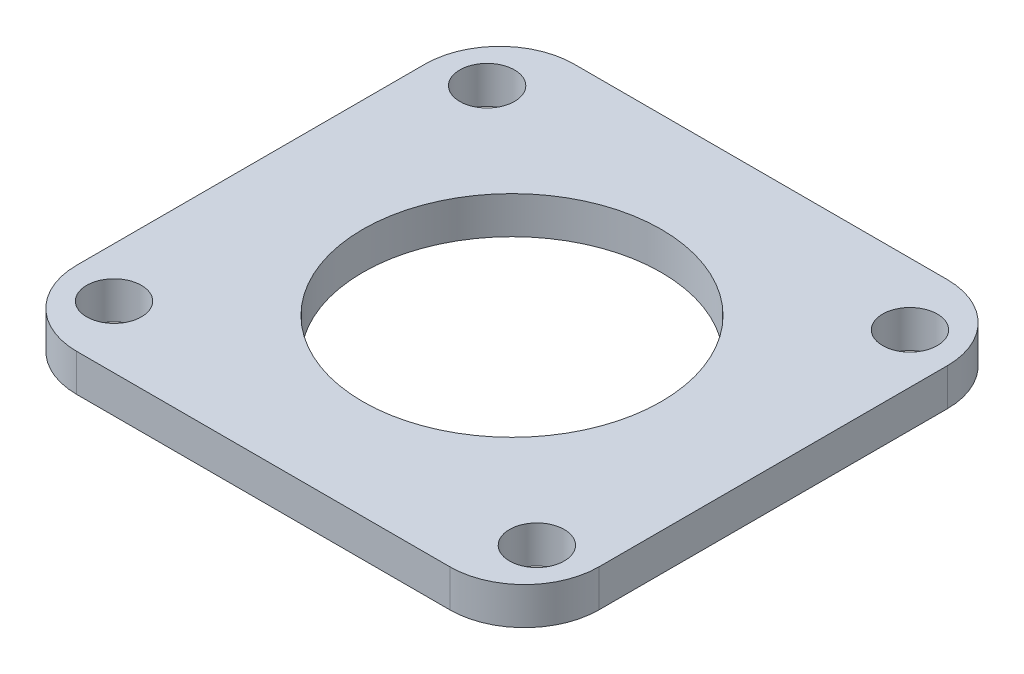
SolidWorks part; units mm, degrees
material "2024 Alloy"
ref_plane "Front Plane" through (0, 0, 0) normal (0, 0, 1) x (1, 0, 0)
ref_plane "Top Plane" through (0, 0, 0) normal (0, 1, 0) x (1, 0, 0)
ref_plane "Right Plane" through (0, 0, 0) normal (1, 0, 0) x (0, 0, -1)
sketch "Sketch1" plane through (0, 0, 0) normal (0, 1, 0) x (1, 0, 0)
  line L0 (-8.5, 7.5) -> (8.5, 7.5) construction
  line L1 (-8.5, 7.5) -> (-8.5, -7.5) construction
  line L2 (-8.5, -7.5) -> (8.5, -7.5) construction
  line L3 (8.5, 7.5) -> (8.5, -7.5) construction
  line L4 (-8.5, 7.5) -> (8.5, -7.5) construction
  line L5 (-8.5, -7.5) -> (8.5, 7.5) construction
  line L7 (-10.5, -10) -> (10.5, -10)
  line L8 (-10.5, -10) -> (-10.5, 10)
  line L9 (-10.5, 10) -> (10.5, 10)
  line L10 (10.5, -10) -> (10.5, 10)
  line L11 (-10.5, -10) -> (10.5, 10) construction
  line L12 (-10.5, 10) -> (10.5, -10) construction
  circle A0 centre (8.5, 7.5) radius 1.1
  circle A1 centre (-8.5, 7.5) radius 1.1
  circle A2 centre (-8.5, -7.5) radius 1.1
  circle A3 centre (8.5, -7.5) radius 1.1
  circle A4 centre (0, 0) radius 6
  point P0 (-8.5, 7.5)
  point P1 (8.5, 7.5)
  point P2 (8.5, -7.5)
  point P3 (-8.5, -7.5)
  point P8 (0, 0)
  point P13 (0, 0)
  dimension "D3" = 2.2
  dimension "D6" = 12
  dimension "D1" = 15
  dimension "D2" = 17
  dimension "D4" = 20
  dimension "D5" = 21
extrude "Boss-Extrude1" add sketch "Sketch1" along normal blind 1.5
fillet "Fillet1" radius 3 4 edges at (10.5, 0.75, -10) (10.5, 0.75, 10) (-10.5, 0.75, 10) (-10.5, 0.75, -10)
